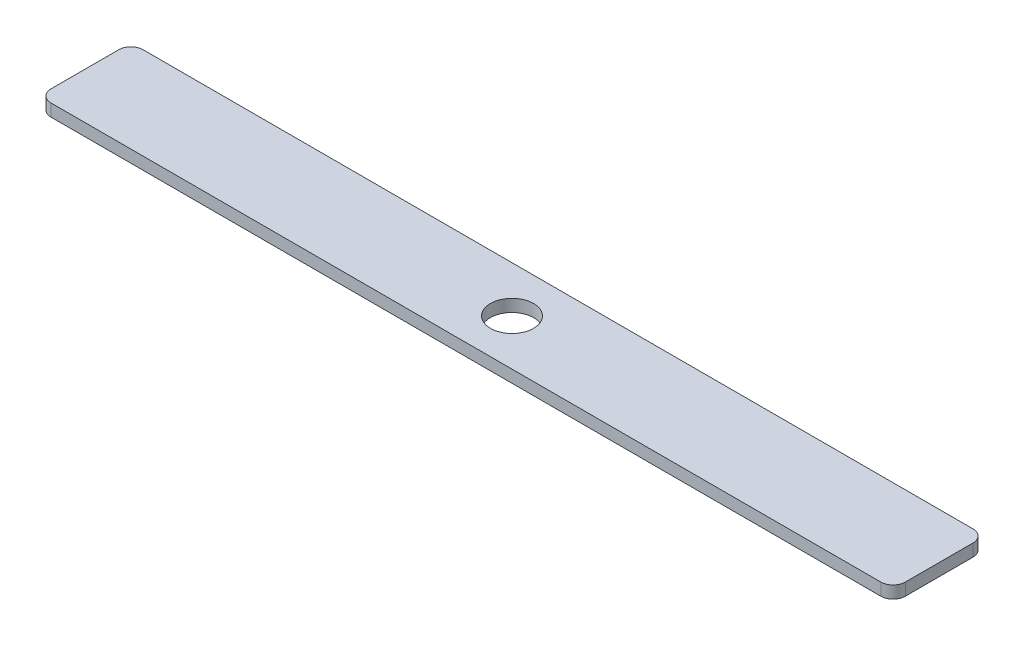
SolidWorks part; units mm, degrees
ref_plane "Front Plane" through (0, 0, 0) normal (0, 0, 1) x (1, 0, 0)
ref_plane "Top Plane" through (0, 0, 0) normal (0, 1, 0) x (1, 0, 0)
ref_plane "Right Plane" through (0, 0, 0) normal (1, 0, 0) x (0, 0, -1)
sketch "Sketch1" plane through (0, 0, 0) normal (0, 1, 0) x (1, 0, 0)
  line L1 (176.5935, -19.05) -> (-176.5935, -19.05)
  line L2 (176.5935, -19.05) -> (176.5935, 19.05)
  line L3 (176.5935, 19.05) -> (-176.5935, 19.05)
  line L4 (-176.5935, -19.05) -> (-176.5935, 19.05)
  line L5 (176.5935, -19.05) -> (-176.5935, 19.05) construction
  line L6 (176.5935, 19.05) -> (-176.5935, -19.05) construction
  circle A0 centre (0, 0) radius 8.9116
  point P0 (0, 0)
  point P8 (0, 0)
  point P9 (0, 0)
extrude "Boss-Extrude1" add sketch "Sketch1" against normal blind 5.08
fillet "Fillet1" radius 5.08 4 edges at (176.5935, -2.54, -19.05) (176.5935, -2.54, 19.05) (-176.5935, -2.54, -19.05) (-176.5935, -2.54, 19.05)
